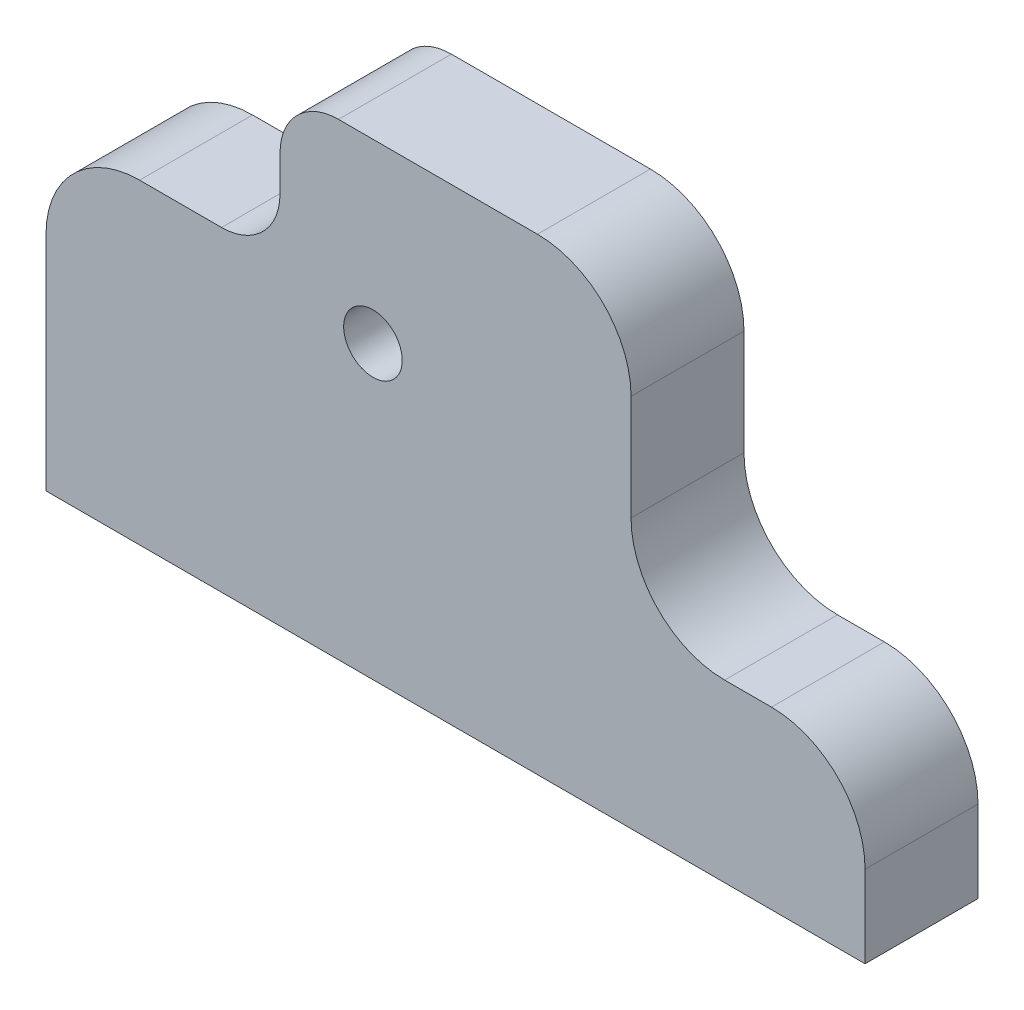
SolidWorks part; units mm, degrees
material "6061 Alloy"
ref_plane "Front" through (0, 0, 0) normal (0, 0, 1) x (1, 0, 0)
ref_plane "Top" through (0, 0, 0) normal (0, 1, 0) x (1, 0, 0)
ref_plane "Right" through (0, 0, 0) normal (1, 0, 0) x (0, 0, -1)
sketch "Sketch1" plane through (0, 0, 0) normal (0, 0, 1) x (1, 0, 0)
  line L0 (0, 0) -> (0, 13.5)
  line L9 (35, 0) -> (0, 0)
  line L15 (10, 20) -> (25, 20)
  line L16 (25, 20) -> (25, 7.5)
  line L17 (25, 7.5) -> (35, 7.5)
  line L18 (35, 7.5) -> (35, 0)
  line L20 (0, 13.5) -> (10, 13.5)
  line L21 (10, 13.5) -> (10, 20)
  dimension "D3" = 13.5
  dimension "D1" = 35
  dimension "D2" = 10
  dimension "D4" = 15
  dimension "D5" = 20
  dimension "D6" = 7.5
extrude "Boss-Extrude1" add sketch "Sketch1" along normal blind 4.826
hole_wizard "M3x0.5 Tapped Hole2" positions "Sketch13" profile "Sketch14" tap size "M3x0.5" standard "ANSI Metric" end condition through all
sketch "Sketch13" plane through (0, 0, 4.826) normal (0, 0, 1) x (1, 0, 0)
  line L2 (35, 0) -> (0, 0) construction
  point P5 (13.9702, 12.44)
  dimension "D1" = 12.44
  dimension "D2" = 13.9702
sketch "Sketch14" plane through (13.9702, 12.44, 4.826) normal (1, 0, 0) x (0, -1, 0)
  line L0 (0, 0) -> (0, 4.826)
  line L1 (0, 4.826) -> (1.25, 4.826)
  line L2 (1.25, 4.826) -> (1.25, 0)
  line L5 (1.25, 0) -> (0, 0)
  line L11 (0, -6.35) -> (0, 107.95) construction
  dimension "Thru Tap Drill Dia." = 2.5
  dimension "Thru Tap Drill Depth" = 4.826
cosmetic thread "Hole Thread1" parameters "D2"=3
sketch "Sketch16" plane through (0, 0, 0) normal (0, -1, 0) x (1, 0, 0)
  line L0 (0, 4.826) -> (0, 0) construction
  line L3 (0, 2.413) -> (42.6944, 2.413) construction
  point P0 (28.73, 2.413)
  point P1 (16.73, 2.413)
  dimension "D1" = 16.73
  dimension "D2" = 12
hole_wizard "M3x0.5 Tapped Hole3" positions "Sketch17" profile "Sketch18" tap size "M3x0.5" standard "ANSI Metric"
sketch "Sketch17" plane through (0, 0, 0) normal (0, -1, 0) x (-1, 0, 0)
  point P0 (-16.73, -2.413)
  point P3 (-28.73, -2.413)
sketch "Sketch18" plane through (16.73, 0, 2.413) normal (1, 0, 0) x (0, 0, -1)
  line L0 (0, 0) -> (0, 5.7511)
  line L1 (0, 5.7511) -> (1.25, 5)
  line L2 (1.25, 5) -> (1.25, 0)
  line L5 (1.25, 0) -> (0, 0)
  line L10 (0, 5.7511) -> (-1.25, 5) construction
  line L11 (0, -6.35) -> (0, 107.95) construction
  dimension "Tap Drill Dia." = 2.5
  dimension "Tap Drill Depth" = 5
  dimension "Drill Angle" = 118
fillet "Fillet1" radius 2.5 2 edges at (10, 13.5, 2.413) (10, 20, 2.413)
chamfer "Chamfer1" [suppressed] distance 13 distance2 10
fillet "Fillet2" radius 4 4 edges at (35, 7.5, 2.413) (25, 7.5, 2.413) (25, 20, 2.413) (0, 13.5, 2.413)
